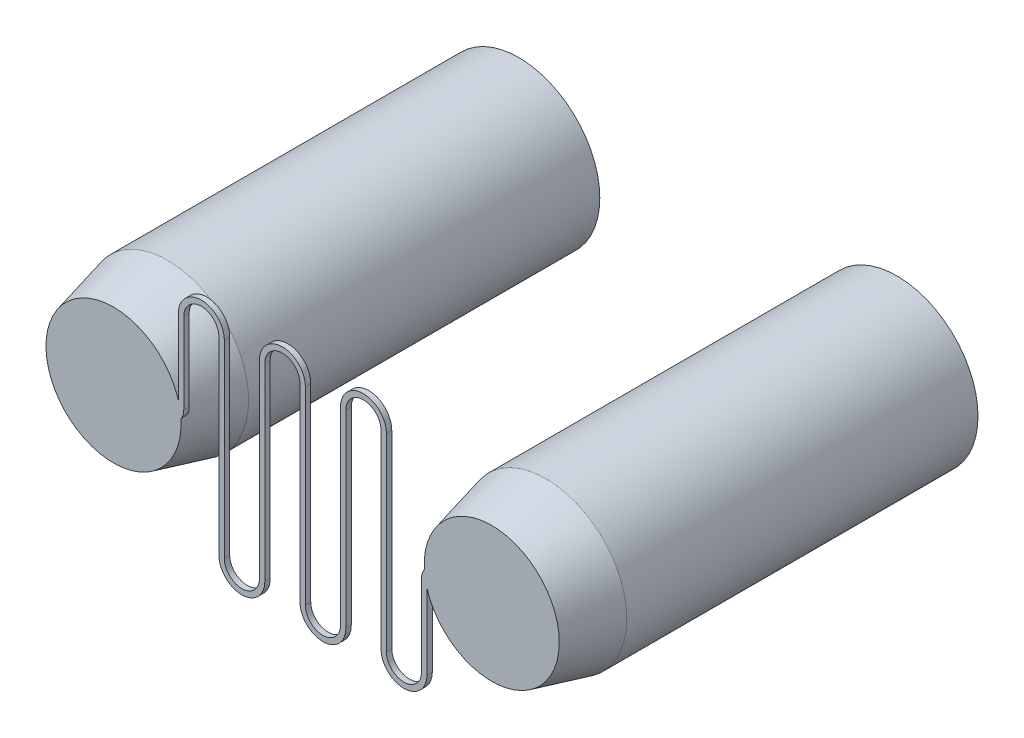
SolidWorks part; units mm, degrees
ref_plane "Front Plane" through (0, 0, 0) normal (0, 0, 1) x (1, 0, 0)
ref_plane "Top Plane" through (0, 0, 0) normal (0, 1, 0) x (1, 0, 0)
ref_plane "Right Plane" through (0, 0, 0) normal (1, 0, 0) x (0, 0, -1)
sketch "Sketch2" plane through (0, 0, 0) normal (0, 0, 1) x (1, 0, 0)
  line L3 (-17.5, -0.2) -> (-13.5, -0.2)
  line L6 (-12.3, 1) -> (-12.3, 7)
  line L9 (-9.7, 7) -> (-9.7, 0)
  line L12 (-9.7, 0) -> (-9.7, -7)
  line L15 (-6.3, -7) -> (-6.3, 0)
  line L18 (-6.3, 0) -> (-6.3, 7)
  line L21 (-3.7, 7) -> (-3.7, 0)
  line L22 (-3.7, 0) -> (-3.7, -7)
  line L23 (-0.3, -7) -> (-0.3, 0)
  line L24 (-0.3, 0) -> (-0.3, 7)
  line L25 (2.3, 7) -> (2.3, 0)
  line L26 (2.3, 0) -> (2.3, -7)
  line L27 (5.7, -7) -> (5.7, -1)
  line L28 (6.5, -0.2) -> (10.5, -0.2)
  line L29 (-17.5, 0.2) -> (-13.5, 0.2)
  line L30 (-12.7, 1) -> (-12.7, 7)
  line L31 (-9.3, 7) -> (-9.3, 0)
  line L32 (-9.3, 0) -> (-9.3, -7)
  line L33 (-6.7, -7) -> (-6.7, 0)
  line L34 (-6.7, 0) -> (-6.7, 7)
  line L35 (-3.3, 7) -> (-3.3, 0)
  line L36 (-3.3, 0) -> (-3.3, -7)
  line L37 (-0.7, -7) -> (-0.7, 0)
  line L38 (-0.7, 0) -> (-0.7, 7)
  line L39 (2.7, 7) -> (2.7, 0)
  line L40 (2.7, 0) -> (2.7, -7)
  line L41 (5.3, -7) -> (5.3, -1)
  line L42 (6.5, 0.2) -> (10.5, 0.2)
  arc A8 (-12.3, 1) -> (-13.5, -0.2) centre (-13.5, 1) cw
  arc A9 (-12.3, 7) -> (-9.7, 7) centre (-11, 7) cw
  arc A10 (-9.7, -7) -> (-6.3, -7) centre (-8, -7) ccw
  arc A11 (-6.3, 7) -> (-3.7, 7) centre (-5, 7) cw
  arc A12 (-3.7, -7) -> (-0.3, -7) centre (-2, -7) ccw
  arc A13 (-0.3, 7) -> (2.3, 7) centre (1, 7) cw
  arc A14 (2.3, -7) -> (5.7, -7) centre (4, -7) ccw
  arc A15 (5.7, -1) -> (6.5, -0.2) centre (6.5, -1) cw
  arc A16 (-12.7, 1) -> (-13.5, 0.2) centre (-13.5, 1) cw
  arc A17 (-12.7, 7) -> (-9.3, 7) centre (-11, 7) cw
  arc A18 (-9.3, -7) -> (-6.7, -7) centre (-8, -7) ccw
  arc A19 (-6.7, 7) -> (-3.3, 7) centre (-5, 7) cw
  arc A20 (-3.3, -7) -> (-0.7, -7) centre (-2, -7) ccw
  arc A21 (-0.7, 7) -> (2.7, 7) centre (1, 7) cw
  arc A22 (2.7, -7) -> (5.3, -7) centre (4, -7) ccw
  arc A23 (5.3, -1) -> (6.5, 0.2) centre (6.5, -1) cw
  arc A24 (-17.5, 0.2) -> (-17.5, -0.2) centre (-17.5, 0) ccw
  arc A25 (10.5, -0.2) -> (10.5, 0.2) centre (10.5, 0) ccw
  point P4 (0, 0)
  point P32 (5.5, 0)
  point P35 (-12.5, 0)
  dimension "D14" = 5
extrude "Boss-Extrude1" add sketch "Sketch2" along normal blind 0.4
ref_plane "Plane1" through (0, 0, 0) normal (0, -1, 0) x (-1, 0, 0)
sketch "Sketch3" plane through (0, 0, 0) normal (0, -1, 0) x (-1, 0, 0)
  line L0 (17.5, -0.4) -> (22.5, -0.4)
  line L2 (17.5, -0.4) -> (17.5, 29.6)
  line L3 (17.5, 29.6) -> (23.5, 29.6)
  line L4 (23.5, 29.6) -> (23.5, 3.6)
  line L5 (23.5, 3.6) -> (22.5, -0.4)
  dimension "D1" = 5
  dimension "D3" = 30
  dimension "D4" = 6
revolve "Revolve1" add sketch "Sketch3" angle 360 about L2
ref_plane "Plane2" through (0, 0, 0) normal (0, -1, 0) x (-1, 0, 0)
sketch "Sketch4" plane through (0, 0, 0) normal (0, -1, 0) x (-1, 0, 0)
  line L0 (-10.5, -0.4) -> (-15.5, -0.4)
  line L2 (-10.5, -0.4) -> (-10.5, 29.6)
  line L3 (-10.5, 29.6) -> (-16.5, 29.6)
  line L4 (-16.5, 29.6) -> (-16.5, 3.6)
  line L5 (-16.5, 3.6) -> (-15.5, -0.4)
  dimension "D1" = 5
  dimension "D3" = 30
  dimension "D4" = 6
revolve "Revolve2" add sketch "Sketch4" angle 360 about L2
